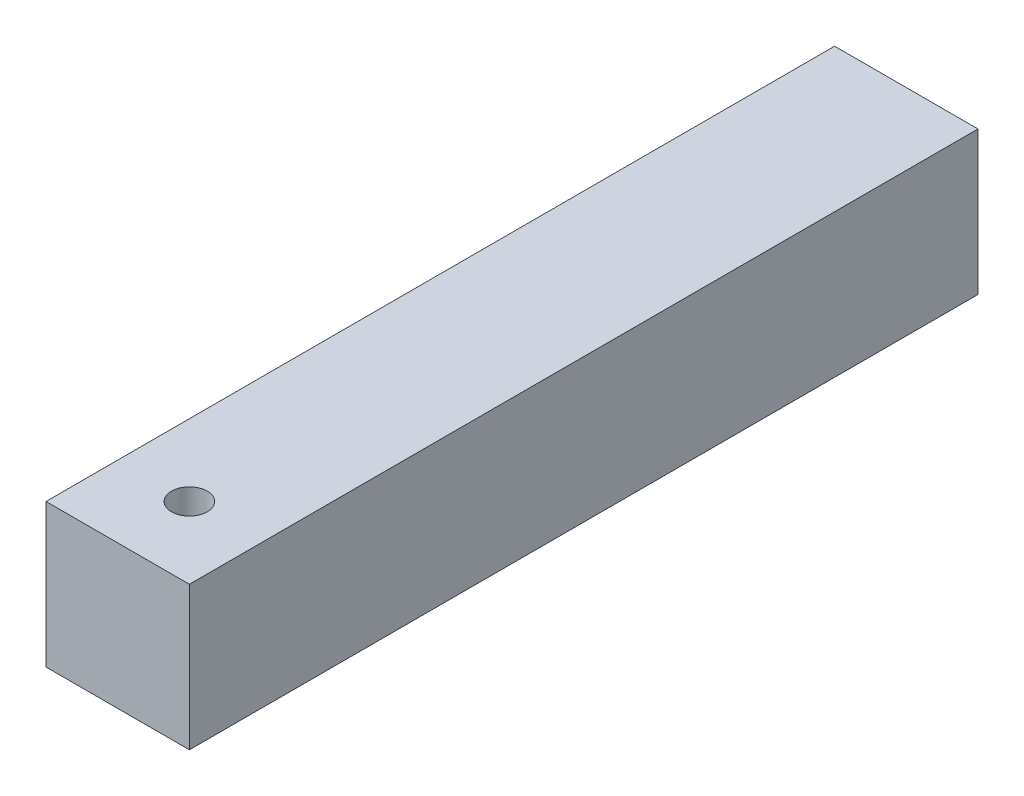
SolidWorks part; units mm, degrees
ref_plane "Front Plane" through (0, 0, 0) normal (0, 0, 1) x (1, 0, 0)
ref_plane "Top Plane" through (0, 0, 0) normal (0, 1, 0) x (1, 0, 0)
ref_plane "Right Plane" through (0, 0, 0) normal (1, 0, 0) x (0, 0, -1)
sketch "Sketch2" plane through (0, 0, 0) normal (0, 0, 1) x (1, 0, 0)
  line L1 (50, 50) -> (-50, 50)
  line L2 (50, 50) -> (50, -50)
  line L3 (50, -50) -> (-50, -50)
  line L4 (-50, 50) -> (-50, -50)
  line L5 (50, 50) -> (-50, -50) construction
  line L6 (50, -50) -> (-50, 50) construction
  point P0 (0, 0)
  dimension "D1" = 100
  dimension "D2" = 100
extrude "Boss-Extrude1" add sketch "Sketch2" against normal blind 550
sketch "Sketch3" plane through (0, 50, 0) normal (0, 1, 0) x (1, 0, 0)
  line L0 (0, 550) -> (0, 0) construction
  line L1 (50, 550) -> (-50, 550) construction
  circle A0 centre (0, 50) radius 12.5
  dimension "D1" = 25
  dimension "D2" = 500
extrude "Cut-Extrude1" cut sketch "Sketch3" against normal blind 500
